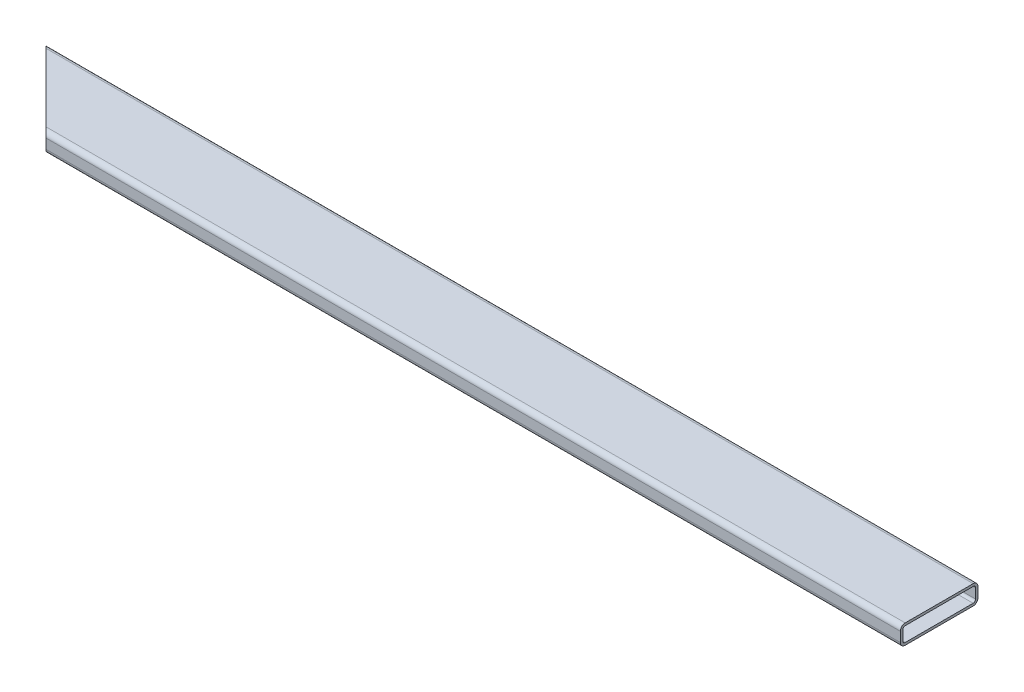
SolidWorks part; units mm, degrees
material "Alloy Steel"
ref_plane "Front Plane" through (0, 0, 0) normal (0, 0, 1) x (1, 0, 0)
ref_plane "Top Plane" through (0, 0, 0) normal (0, 1, 0) x (1, 0, 0)
ref_plane "Right Plane" through (0, 0, 0) normal (1, 0, 0) x (0, 0, -1)
sketch "Sketch1" plane through (0, 0, 0) normal (1, 0, 0) x (0, 0, -1)
  line L1 (0, 0) -> (101.6, 0)
  line L2 (0, 0) -> (0, 25.4)
  line L3 (0, 25.4) -> (101.6, 25.4)
  line L4 (101.6, 0) -> (101.6, 25.4)
  dimension "D1" = 25.4
  dimension "D2" = 101.6
extrude "Boss-Extrude1" add sketch "Sketch1" along normal blind 1219.2
fillet "Fillet1" radius 6.35 4 edges at (609.6, 0, -101.6) (609.6, 25.4, -101.6) (609.6, 0, 0) (609.6, 25.4, 0)
shell "Shell1" thickness 3.175
sketch "Sketch2" plane through (0, 25.4, 0) normal (0, 1, 0) x (1, 0, 0)
  line L0 (0, 101.6) -> (101.6, 0)
  line L1 (1219.2, 0) -> (0, 0) construction
  line L2 (0, 101.6) -> (0, 0)
  line L3 (0, 0) -> (101.6, 0)
  line L4 (0, 101.6) -> (1219.2, 101.6) construction
  dimension "D1" = 45
extrude "Cut-Extrude1" cut sketch "Sketch2" against normal blind 25.4
